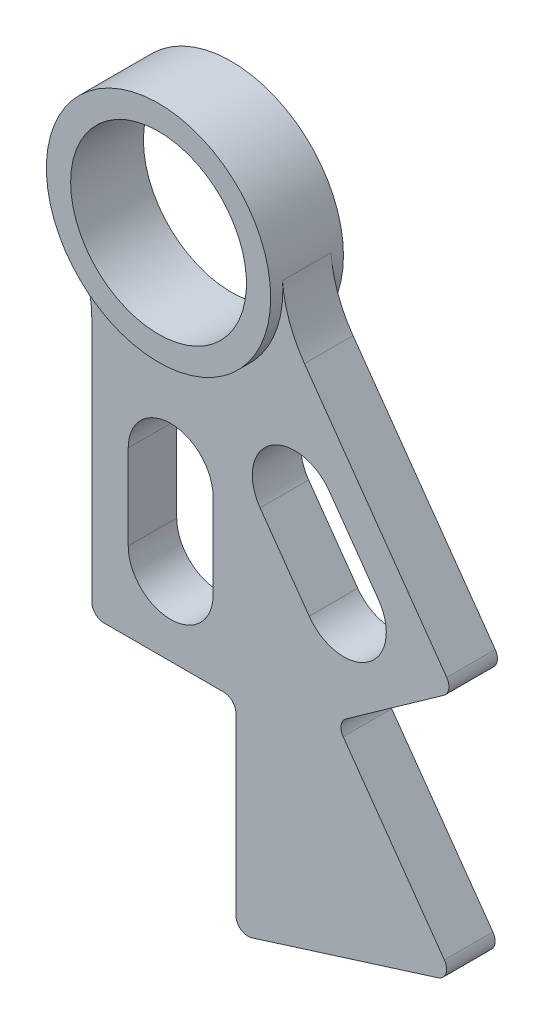
SolidWorks part; units mm, degrees
material "AISI 4130 Steel, annealed at 865C"
ref_plane "X-Y Datum" through (0, 0, 0) normal (0, 0, 1) x (1, 0, 0)
ref_plane "X-Z Datum" through (0, 0, 0) normal (0, 1, 0) x (1, 0, 0)
ref_plane "Y-Z Datum" through (0, 0, 0) normal (1, 0, 0) x (0, 0, -1)
sketch "Sketch1" plane through (0, 0, 0) normal (0, 0, 1) x (1, 0, 0)
  line L0 (0, -39.0706) -> (0, -27.9581) construction
  line L1 (-5.5562, -39.0706) -> (-5.5562, -27.9581)
  line L2 (5.5562, -39.0706) -> (5.5562, -27.9581)
  line L3 (22.6674, -31.9787) -> (16.2412, -22.9128) construction
  line L4 (18.1344, -35.1918) -> (11.7082, -26.1259)
  line L5 (27.2003, -28.7657) -> (20.7742, -19.6997)
  line L6 (-10.3187, -15.7343) -> (-10.3187, -49.3893)
  line L7 (-10.3187, -49.3893) -> (10.3187, -49.3893)
  line L10 (20.2161, -46.3643) -> (37.0529, -34.43)
  line L11 (37.0529, -34.43) -> (17.5173, -6.8694)
  line L12 (0, -39.0706) -> (0, 0) construction
  line L13 (0, 0) -> (22.6674, -31.9787) construction
  line L14 (0, -44.6268) -> (0, -49.3893) construction
  line L15 (25.8805, -36.5117) -> (28.6345, -40.3971) construction
  line L16 (23.9872, -24.2327) -> (27.8727, -21.4786) construction
  line L17 (-5.5562, -33.5143) -> (-10.3187, -33.5143) construction
  line L18 (-10.3187, -17.6393) -> (10.3187, -17.6393) construction
  line L19 (10.3187, -17.6393) -> (10.3187, -49.3893) construction
  line L20 (5.5562, -33.5143) -> (10.3187, -33.5143) construction
  line L21 (0, -22.4018) -> (0, -17.6393) construction
  line L22 (20.2161, -46.3643) -> (1.8556, -20.4616) construction
  line L23 (1.8556, -20.4616) -> (18.6924, -8.5272) construction
  line L24 (14.9213, -30.6589) -> (11.0359, -33.4129) construction
  line L25 (13.0281, -18.3798) -> (10.274, -14.4944) construction
  line L29 (8.5407, -49.3893) -> (8.5407, -79.8693)
  line L31 (8.5407, -79.8693) -> (39.2928, -70.2028)
  line L33 (39.2928, -70.2028) -> (21.6667, -45.3361)
  circle A0 centre (0, 0) radius 11.5062
  arc A1 (-5.5562, -39.0706) -> (5.5562, -39.0706) centre (0, -39.0706) ccw
  arc A2 (5.5562, -27.9581) -> (-5.5562, -27.9581) centre (0, -27.9581) ccw
  arc A3 (18.1344, -35.1918) -> (27.2003, -28.7657) centre (22.6674, -31.9787) ccw
  arc A4 (20.7742, -19.6997) -> (11.7082, -26.1259) centre (16.2412, -22.9128) ccw
  arc A5 (14.6392, 1.1103) -> (-12.5852, -7.5598) centre (0, 0) ccw
  arc A6 (17.5173, -6.8694) -> (14.6392, 1.1103) centre (30.4687, 2.3108) cw
  arc A7 (-10.3187, -15.7343) -> (-12.5852, -7.5598) centre (-26.1937, -15.7343) ccw
  arc A14 (-12.5852, -7.5598) -> (14.6392, 1.1103) centre (0, 0) ccw
  point P2 (8.5407, -49.3893)
  point P5 (0, -33.5143)
  point P11 (19.4543, -27.4458)
  point P17 (21.6667, -45.3361)
  point P24 (28.6345, -40.3971)
  point P31 (0, -49.3893)
  point P39 (25.8805, -36.5117)
  dimension "D1" = 23.0124
  dimension "D2" = 14.6812
  dimension "D8" = 15.875
  dimension "D9" = 35.33
  dimension "D3" = 1.778
  dimension "D4" = 4.7625
  dimension "D5" = 31.75
  dimension "D6" = 2.032
  dimension "D7" = 1.905
  dimension "D10" = 1.778
  dimension "D11" = 30.48
extrude "Boss-Extrude1" add sketch "Sketch1" along normal mid plane 9.525 contours A5 A14 A0
sketch "Sketch5" plane through (0, 0, 0) normal (0, 0, 1) x (1, 0, 0)
  line L0 (0, -39.0706) -> (0, -27.9581) construction
  line L1 (-5.5562, -39.0706) -> (-5.5562, -27.9581)
  line L2 (5.5562, -39.0706) -> (5.5562, -27.9581)
  line L3 (22.6674, -31.9787) -> (16.2412, -22.9128) construction
  line L4 (18.1344, -35.1918) -> (11.7082, -26.1259)
  line L5 (27.2003, -28.7657) -> (20.7742, -19.6997)
  line L6 (-10.3187, -15.7343) -> (-10.3187, -49.3893)
  line L7 (-10.3187, -49.3893) -> (10.3187, -49.3893)
  line L8 (20.2161, -46.3643) -> (37.0529, -34.43)
  line L9 (37.0529, -34.43) -> (17.5173, -6.8694)
  line L10 (0, -39.0706) -> (0, 0) construction
  line L11 (0, 0) -> (22.6674, -31.9787) construction
  line L12 (0, -44.6268) -> (0, -49.3893) construction
  line L13 (25.8805, -36.5117) -> (28.6345, -40.3971) construction
  line L14 (23.9872, -24.2327) -> (27.8727, -21.4786) construction
  line L15 (-5.5562, -33.5143) -> (-10.3187, -33.5143) construction
  line L16 (-10.3187, -17.6393) -> (10.3187, -17.6393) construction
  line L17 (10.3187, -17.6393) -> (10.3187, -49.3893) construction
  line L18 (5.5562, -33.5143) -> (10.3187, -33.5143) construction
  line L19 (0, -22.4018) -> (0, -17.6393) construction
  line L20 (20.2161, -46.3643) -> (1.8556, -20.4616) construction
  line L21 (1.8556, -20.4616) -> (18.6924, -8.5272) construction
  line L22 (14.9213, -30.6589) -> (11.0359, -33.4129) construction
  line L23 (13.0281, -18.3798) -> (10.274, -14.4944) construction
  line L24 (8.5407, -49.3893) -> (8.5407, -76.0593)
  line L25 (8.5407, -76.0593) -> (37.0896, -67.0944)
  line L26 (37.0896, -67.0944) -> (21.6667, -45.3361)
  circle A0 centre (0, 0) radius 11.5062
  arc A1 (-5.5562, -39.0706) -> (5.5562, -39.0706) centre (0, -39.0706) ccw
  arc A2 (5.5562, -27.9581) -> (-5.5562, -27.9581) centre (0, -27.9581) ccw
  arc A3 (18.1344, -35.1918) -> (27.2003, -28.7657) centre (22.6674, -31.9787) ccw
  arc A4 (20.7742, -19.6997) -> (11.7082, -26.1259) centre (16.2412, -22.9128) ccw
  arc A5 (14.6392, 1.1103) -> (-12.5852, -7.5598) centre (0, 0) ccw
  arc A6 (17.5173, -6.8694) -> (14.6392, 1.1103) centre (30.4687, 2.3108) cw
  arc A7 (-10.3187, -15.7343) -> (-12.5852, -7.5598) centre (-26.1937, -15.7343) ccw
  arc A8 (-12.5852, -7.5598) -> (14.6392, 1.1103) centre (0, 0) ccw
  point P2 (8.5407, -49.3893)
  point P5 (0, -33.5143)
  point P11 (19.4543, -27.4458)
  point P17 (21.6667, -45.3361)
  point P24 (28.6345, -40.3971)
  point P31 (0, -49.3893)
  point P39 (25.8805, -36.5117)
  dimension "D1" = 23.0124
  dimension "D3" = 15.875
  dimension "D7" = 14.6812
  dimension "D2" = 4.7625
  dimension "D4" = 31.75
  dimension "D5" = 1.905
  dimension "D6" = 2.032
  dimension "D8" = 35.33
  dimension "D9" = 1.778
  dimension "D10" = 1.778
  dimension "D11" = 26.67
extrude "Boss-Extrude2" add sketch "Sketch5" along normal mid plane 6.35
fillet "Fillet2" radius 1.5875 6 edges at (21.6667, -45.3361, 0) (37.0896, -67.0944, 0) (37.0529, -34.43, 0) (8.5407, -76.0593, 0) (8.5407, -49.3893, 0) (-10.3187, -49.3893, 0)
sketch "Sketch2" plane through (0, 0, 0) normal (0, 0, 1) x (1, 0, 0)
  line L0 (0, -39.0706) -> (0, -27.9581) construction
  line L1 (-5.5562, -39.0706) -> (-5.5562, -27.9581)
  line L2 (5.5562, -39.0706) -> (5.5562, -27.9581)
  line L3 (22.6674, -31.9787) -> (16.2412, -22.9128) construction
  line L4 (18.1344, -35.1918) -> (11.7082, -26.1259)
  line L5 (27.2003, -28.7657) -> (20.7742, -19.6997)
  line L6 (-10.3187, -15.7343) -> (-10.3187, -49.3893)
  line L7 (-10.3187, -49.3893) -> (10.3187, -49.3893)
  line L10 (20.2161, -46.3643) -> (37.0529, -34.43)
  line L11 (37.0529, -34.43) -> (17.5173, -6.8694)
  line L12 (0, -39.0706) -> (0, 0) construction
  line L13 (0, 0) -> (22.6674, -31.9787) construction
  line L14 (0, -44.6268) -> (0, -49.3893) construction
  line L15 (25.8805, -36.5117) -> (28.6345, -40.3971) construction
  line L16 (23.9872, -24.2327) -> (27.8727, -21.4786) construction
  line L17 (-5.5562, -33.5143) -> (-10.3187, -33.5143) construction
  line L18 (-10.3187, -17.6393) -> (10.3187, -17.6393) construction
  line L19 (10.3187, -17.6393) -> (10.3187, -49.3893) construction
  line L20 (5.5562, -33.5143) -> (10.3187, -33.5143) construction
  line L21 (0, -22.4018) -> (0, -17.6393) construction
  line L22 (20.2161, -46.3643) -> (1.8556, -20.4616) construction
  line L23 (1.8556, -20.4616) -> (18.6924, -8.5272) construction
  line L24 (14.9213, -30.6589) -> (11.0359, -33.4129) construction
  line L25 (13.0281, -18.3798) -> (10.274, -14.4944) construction
  line L30 (20.2161, -46.3643) -> (10.3187, -32.4012)
  line L32 (10.3187, -32.4012) -> (10.3187, -49.3893)
  arc A1 (-5.5562, -39.0706) -> (5.5562, -39.0706) centre (0, -39.0706) ccw
  arc A2 (5.5562, -27.9581) -> (-5.5562, -27.9581) centre (0, -27.9581) ccw
  arc A3 (18.1344, -35.1918) -> (27.2003, -28.7657) centre (22.6674, -31.9787) ccw
  arc A4 (20.7742, -19.6997) -> (11.7082, -26.1259) centre (16.2412, -22.9128) ccw
  arc A6 (17.5173, -6.8694) -> (14.6392, 1.1103) centre (30.4687, 2.3108) cw
  arc A7 (-10.3187, -15.7343) -> (-12.5852, -7.5598) centre (-26.1937, -15.7343) ccw
  arc A14 (-12.5852, -7.5598) -> (14.6392, 1.1103) centre (0, 0) ccw
  point P5 (0, -33.5143)
  point P11 (19.4543, -27.4458)
  point P24 (28.6345, -40.3971)
  point P31 (0, -49.3893)
  point P39 (25.8805, -36.5117)
  dimension "D1" = 7.5598
  dimension "D2" = 14.6812
  dimension "D8" = 15.875
  dimension "D9" = 35.33
  dimension "D3" = 20.6375
  dimension "D4" = 4.7625
  dimension "D5" = 31.75
  dimension "D6" = 2.032
  dimension "D7" = 1.905
sketch "Sketch3" plane through (0, 0, 4.7625) normal (0, 0, 1) x (1, 0, 0)
  point P0 (0, 0)
sketch "Sketch4" plane through (0, 0, 0) normal (0, 0, -1) x (-1, 0, 0)
  point P0 (0, 0)
